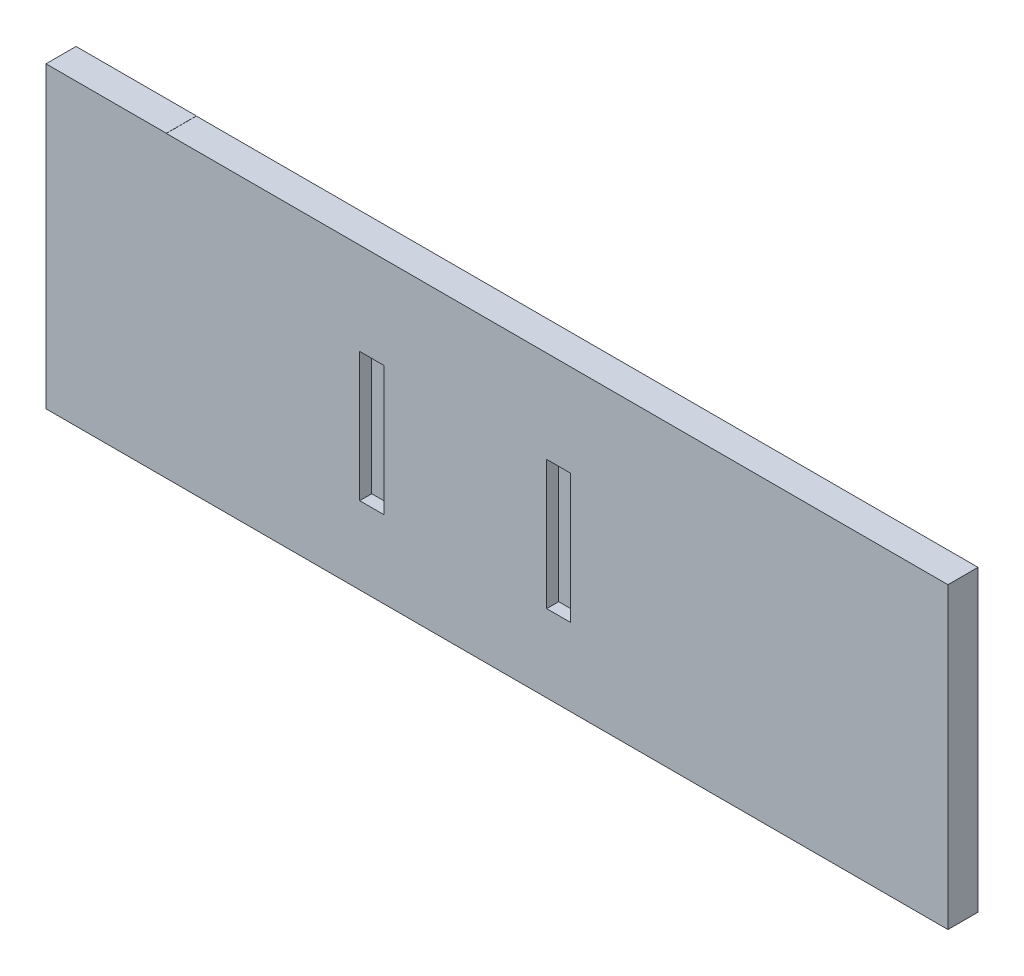
SolidWorks part; units mm, degrees
ref_plane "Płaszczyzna przednia" through (0, 0, 0) normal (0, 0, 1) x (1, 0, 0)
ref_plane "Płaszczyzna górna" through (0, 0, 0) normal (0, 1, 0) x (1, 0, 0)
ref_plane "Płaszczyzna prawa" through (0, 0, 0) normal (1, 0, 0) x (0, 0, -1)
sketch "Szkic1" plane through (0, 0, 0) normal (0, 0, 1) x (1, 0, 0)
  line L0 (0, 0) -> (-1300, 0) construction
  line L1 (-1300, 0) -> (-1300, 496.7477)
  line L2 (-1300, 496.7477) -> (0, 496.7477)
  line L3 (0, 496.7477) -> (0, 0)
  line L4 (0, 0) -> (-1300, 0)
  dimension "D1" = 1300
extrude "Dodanie-wyciągnięcie1" add sketch "Szkic1" along normal blind 50
ref_plane "Płaszczyzna1" through (0, 0, 60) normal (0, 0, 1) x (1, 0, 0)
sketch "Szkic2" plane through (0, 0, 60) normal (0, 0, 1) x (1, 0, 0)
  line L0 (-978.3163, 248.3739) -> (-978.3163, 343.5668)
  line L1 (-978.3163, 343.5668) -> (-938.3163, 343.5668)
  line L2 (-938.3163, 343.5668) -> (-938.3163, 128.5668)
  line L3 (-938.3163, 128.5668) -> (-978.3163, 128.5668)
  line L4 (-978.3163, 128.5668) -> (-978.3163, 248.3739)
  line L5 (-938.3163, 248.3739) -> (-667.3894, 248.3739) construction
  line L6 (-667.3894, 248.3739) -> (-667.3894, 343.5668)
  line L7 (-667.3894, 343.5668) -> (-627.3894, 343.5668)
  line L8 (-627.3894, 343.5668) -> (-627.3894, 128.5668)
  line L9 (-627.3894, 128.5668) -> (-667.3894, 128.5668)
  line L10 (-667.3894, 128.5668) -> (-667.3894, 248.3739)
  dimension "D1" = 215
  dimension "D2" = 40
  dimension "D3" = 40
extrude "Wytnij-wyciągnięcie1" cut sketch "Szkic2" against normal blind 30 contours L4 L0 L1 L2 L3 | L10 L6 L7 L8 L9
ref_plane "Płaszczyzna2" through (0, 0, 0) normal (0, -1, 0) x (-1, 0, 0)
sketch "Szkic3" plane through (0, 0, 0) normal (0, -1, 0) x (-1, 0, 0)
  line L0 (1300, 0) -> (1500.0989, 0)
  line L1 (1500.0989, 0) -> (1500.0989, -50)
  line L2 (1500.0989, -50) -> (1300, -50)
  line L3 (1300, -50) -> (1300, 0)
extrude "Dodanie-wyciągnięcie2" add sketch "Szkic3" against normal blind 497
